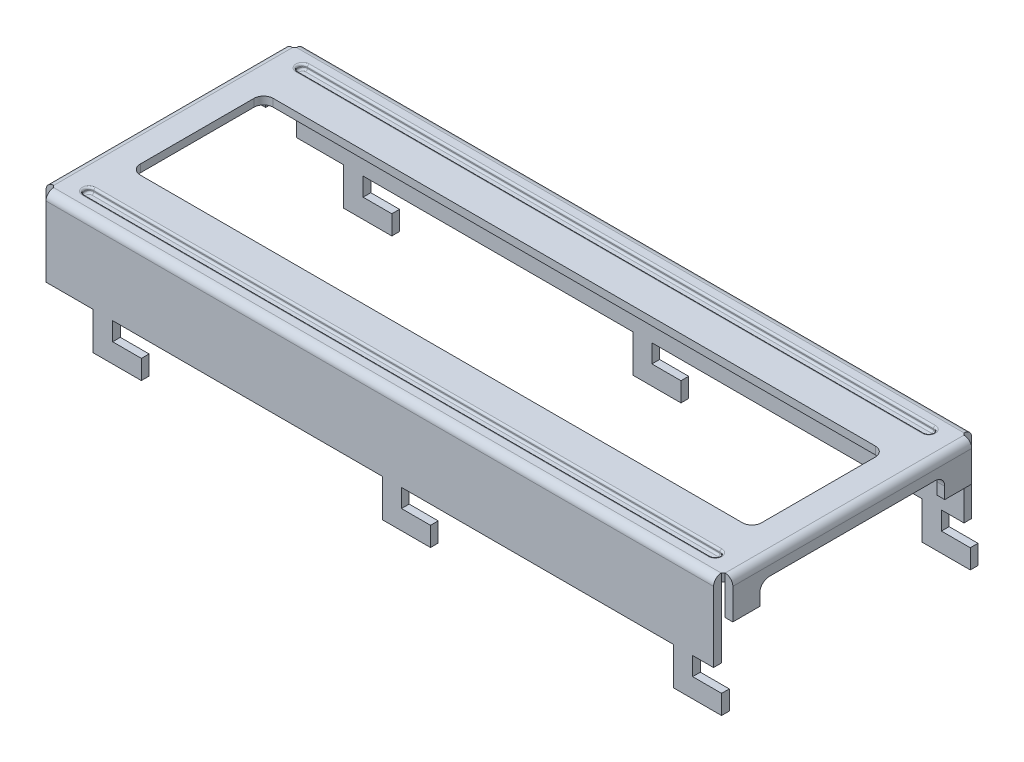
SolidWorks part; units mm, degrees
ref_plane "Front Plane" through (0, 0, 0) normal (0, 0, 1) x (1, 0, 0)
ref_plane "Top Plane" through (0, 0, 0) normal (0, 1, 0) x (1, 0, 0)
ref_plane "Right Plane" through (0, 0, 0) normal (1, 0, 0) x (0, 0, -1)
sketch "Sketch1" plane through (0, 0, 0) normal (0, 1, 0) x (1, 0, 0)
  line L1 (-35.65, 13.4) -> (35.65, 13.4)
  line L2 (-35.65, 13.4) -> (-35.65, -13.4)
  line L3 (-35.65, -13.4) -> (35.65, -13.4)
  line L4 (35.65, 13.4) -> (35.65, -13.4)
extrude "Boss-Extrude1" add sketch "Sketch1" along normal blind 0.8
sketch "Sketch2" plane through (0, 0, 0) normal (0, -1, 0) x (1, 0, 0)
  line L8 (34.85, -12.6) -> (34.85, 12.6)
  line L9 (34.85, 12.6) -> (-34.85, 12.6)
  line L10 (-34.85, 12.6) -> (-34.85, -12.6)
  line L11 (-34.85, -12.6) -> (34.85, -12.6)
  line L12 (34.85, -12.6) -> (34.85, 12.6)
  line L13 (34.85, 12.6) -> (-34.85, 12.6)
  line L14 (-34.85, 12.6) -> (-34.85, -12.6)
  line L15 (-34.85, -12.6) -> (34.85, -12.6)
  line L16 (35.65, -13.4) -> (35.65, 13.4)
  line L17 (35.65, 13.4) -> (-35.65, 13.4)
  line L18 (-35.65, 13.4) -> (-35.65, -13.4)
  line L19 (-35.65, -13.4) -> (35.65, -13.4)
  line L20 (35.65, -13.4) -> (35.65, 13.4)
  line L21 (35.65, 13.4) -> (-35.65, 13.4)
  line L22 (-35.65, 13.4) -> (-35.65, -13.4)
  line L23 (-35.65, -13.4) -> (35.65, -13.4)
  dimension "D1" = 0.8
  dimension "D2" = 0
extrude "Boss-Extrude2" add sketch "Sketch2" along normal blind 7.3
sketch "Sketch5" plane through (-35.65, 0, 0) normal (-1, 0, 0) x (0, 0, 1)
  line L11 (-12.4, 0) -> (-12.6, 0)
  line L12 (-12.6, -7.3) -> (-12.6, 0)
  line L13 (-12.4, 0) -> (-12.4, -3.2)
  line L14 (-12.4, -3.2) -> (-9.6, -3.2)
  line L15 (-9.6, -3.2) -> (-9.6, -2)
  line L16 (12.6, 0) -> (12.6, -7.3)
  line L17 (12.6, 0) -> (12.4, 0)
  line L18 (12.4, -3.2) -> (12.4, 0)
  line L19 (9.6, -3.2) -> (12.4, -3.2)
  line L20 (9.6, -2) -> (9.6, -3.2)
  line L21 (-8.6, -1) -> (8.6, -1)
  line L22 (-12.6, -7.3) -> (12.6, -7.3)
  line L25 (13.4, 0.8) -> (13.4, 0)
  line L26 (12.6, 0.8) -> (13.4, 0.8)
  line L29 (-12.6, 0.8) -> (-13.4, 0.8)
  line L30 (-13.4, 0.8) -> (-13.4, 0)
  arc A2 (-8.6, -1) -> (-9.6, -2) centre (-8.6, -2) ccw
  arc A3 (9.6, -2) -> (8.6, -1) centre (8.6, -2) ccw
  arc A5 (13.4, 0) -> (12.6, 0.8) centre (12.6, 0) ccw
  arc A7 (-12.6, 0.8) -> (-13.4, 0) centre (-12.6, 0) ccw
extrude "Cut-Extrude1" cut sketch "Sketch5" against normal through all
sketch "Sketch9" plane through (0, 0, 13.4) normal (0, 0, 1) x (1, 0, 0)
  line L0 (-35.65, 0.8) -> (-34.85, 0.8)
  line L1 (34.65, -7.3) -> (34.65, 0)
  line L2 (-34.65, 0) -> (-34.65, -7.3)
  line L3 (-34.65, 0) -> (-34.85, 0)
  line L4 (35.65, 0.8) -> (35.65, 0)
  line L5 (-35.65, 0.8) -> (-35.65, 0)
  line L6 (34.65, -7.3) -> (35.65, -7.3)
  line L7 (35.65, -3.2) -> (35.65, -7.3)
  line L8 (-34.65, -7.3) -> (-35.65, -7.3)
  line L9 (-35.65, -3.2) -> (-35.65, -7.3)
  line L10 (-35.65, -3.2) -> (-34.85, -3.2)
  line L11 (-34.85, -3.2) -> (-34.85, 0)
  line L12 (34.85, 0) -> (34.65, 0)
  line L13 (34.85, 0) -> (34.85, -3.2)
  line L14 (34.85, -3.2) -> (35.65, -3.2)
  line L15 (34.65, 0) -> (34.85, 0)
  line L16 (35.65, -7.3) -> (35.65, -3.2)
  line L17 (-35.65, -7.3) -> (-34.65, -7.3)
  line L18 (34.85, 0.8) -> (35.65, 0.8)
  line L19 (-35.65, -3.2) -> (-35.65, -7.3)
  arc A0 (-34.85, 0.8) -> (-35.65, 0) centre (-34.85, 0) ccw
  arc A1 (35.65, 0) -> (34.85, 0.8) centre (34.85, 0) ccw
  line M2 (35.65, 0) -> (-35.65, 0)
  line M3 (-35.65, 0) -> (-35.65, -7.3)
  line M4 (-35.65, -7.3) -> (35.65, -7.3)
  line M5 (35.65, -7.3) -> (35.65, 0)
extrude "Cut-Extrude4" cut sketch "Sketch9" against normal through all contours A0 L0 L5 | L11 L10 L2 M3 M4 M2 | L14 L13 L1 M2 M4 M5 | L4 A1 L18
sketch "Sketch10" plane through (0, 0.8, 0) normal (0, 1, 0) x (1, 0, 0)
  line L0 (-34.65, -12.6) -> (-34.65, -13.4) construction
  line L1 (-34.65, -12.6) -> (-34.65, -13.4)
  line L2 (-34.85, -12.4) -> (-35.65, -12.4) construction
  line L3 (-34.85, -12.4) -> (-35.65, -12.4)
  line L4 (-34.65, -12.6) -> (-34.85, -12.4)
  line L7 (-35.65, -12.4) -> (-35.65, -13.4)
  line L8 (-35.65, -12.6) -> (-35.65, -13.4) construction
  line L9 (-35.65, -13.4) -> (-34.65, -13.4)
  line L10 (35.65, -13.4) -> (34.65, -13.4)
  line L11 (35.65, -12.4) -> (35.65, -13.4)
  line L12 (34.65, -12.6) -> (34.85, -12.4)
  line L13 (34.85, -12.4) -> (35.65, -12.4)
  line L14 (34.65, -12.6) -> (34.65, -13.4)
  line L15 (34.65, 12.6) -> (34.65, 13.4)
  line L16 (34.85, 12.4) -> (35.65, 12.4)
  line L17 (34.65, 12.6) -> (34.85, 12.4)
  line L18 (35.65, 12.4) -> (35.65, 13.4)
  line L19 (35.65, 13.4) -> (34.65, 13.4)
  line L20 (-35.65, 13.4) -> (-34.65, 13.4)
  line L21 (-35.65, 12.4) -> (-35.65, 13.4)
  line L22 (-34.65, 12.6) -> (-34.85, 12.4)
  line L23 (-34.85, 12.4) -> (-35.65, 12.4)
  line L24 (-34.65, 12.6) -> (-34.65, 13.4)
  point P10 (0, 0)
extrude "Cut-Extrude5" cut sketch "Sketch10" against normal through all
sketch "Sketch13" plane through (0, -7.3, 0) normal (0, -1, 0) x (1, 0, 0)
  line L0 (32.4798, 12.6) -> (32.4798, 13.4)
  line L1 (30.4798, 12.6) -> (32.4798, 12.6)
  line L2 (30.4798, 13.4) -> (30.4798, 12.6)
  line L3 (32.4798, 13.4) -> (30.4798, 13.4)
  line L4 (32.302, -12.6) -> (32.302, -13.4)
  line L5 (32.4798, 13.4) -> (32.4798, 12.6)
  line L6 (2.25, -12.6) -> (0.2673, -12.6)
  line L7 (0.2673, -13.4) -> (2.25, -13.4)
  line L8 (-27.7327, -12.6) -> (-29.75, -12.6)
  line L9 (2.25, 13.4) -> (2.25, 12.6)
  line L10 (-29.75, -13.4) -> (-27.7327, -13.4)
  line L11 (30.4798, 12.6) -> (30.4798, 13.4)
  line L13 (0.2673, 12.6) -> (0.2673, 13.4)
  line L15 (-27.7327, 13.4) -> (-27.7327, 12.6)
  line L17 (-29.75, 12.6) -> (-29.75, 13.4)
  line L20 (-34.65, -12.6) -> (34.65, -12.6) construction
  line L21 (-34.65, -13.4) -> (34.65, -13.4) construction
  line L22 (34.65, 12.6) -> (-34.65, 12.6) construction
  line L23 (34.65, 13.4) -> (-34.65, 13.4) construction
  line L24 (-29.75, 13.4) -> (-27.7327, 13.4)
  line L25 (-27.7327, 12.6) -> (-29.75, 12.6)
  line L26 (0.2673, 13.4) -> (2.25, 13.4)
  line L27 (2.25, 12.6) -> (0.2673, 12.6)
  line L28 (32.4798, 12.6) -> (32.4798, 13.4)
  line L29 (-29.75, -12.6) -> (-29.75, -13.4)
  line L30 (-27.7327, -13.4) -> (-27.7327, -12.6)
  line L31 (0.2673, -12.6) -> (0.2673, -13.4)
  line L32 (30.302, -12.6) -> (30.302, -13.4)
  line L33 (2.25, -13.4) -> (2.25, -12.6)
  line L34 (32.302, -13.4) -> (32.302, -12.6)
  line L35 (32.302, -13.4) -> (30.302, -13.4)
  line L36 (30.302, -13.4) -> (30.302, -12.6)
  line L37 (30.302, -12.6) -> (32.302, -12.6)
  line L38 (32.302, -12.6) -> (32.302, -13.4)
  point P17 (0, 0)
  point P19 (0, 0)
  point P33 (0, 0)
  point P34 (0, 0)
  point P37 (0, 0)
  point P38 (0, 0)
  point P39 (0, 0)
  line M3 (34.65, 13.4) -> (-34.65, 13.4)
  line M5 (-34.65, 12.6) -> (34.65, 12.6)
  dimension "D1" = 2
  dimension "D2" = 2
extrude "Bitis" add sketch "Sketch13" along normal blind 1.9 contours L2 L0 M3 M5 | L37 L32 L35 L4 | L7 L33 L6 L31 | L24 L15 L25 L17 | L27 L13 L26 L9 | L8 L29 L10 L30
sketch "Sketch14" plane through (0, -9.2, 0) normal (0, -1, 0) x (1, 0, 0)
  line L0 (30.302, -12.6) -> (30.302, -13.4) construction
  line L8 (-29.75, 13.4) -> (-29.75, 12.6)
  line L9 (-29.75, 12.6) -> (-24.75, 12.6)
  line L10 (-24.75, 12.6) -> (-24.75, 13.4)
  line L11 (-24.75, 13.4) -> (-29.75, 13.4)
  line L12 (0.2673, -13.4) -> (5.2673, -13.4)
  line L13 (-24.75, -13.4) -> (-24.75, -12.6)
  line L14 (5.2673, 12.6) -> (5.2673, 13.4)
  line L15 (5.2673, 13.4) -> (0.2673, 13.4)
  line L16 (0.2673, 13.4) -> (0.2673, 12.6)
  line L17 (0.2673, 12.6) -> (5.2673, 12.6)
  line L18 (35.4798, 13.4) -> (30.4798, 13.4)
  line L19 (30.4798, 13.4) -> (30.4798, 12.6)
  line L20 (30.4798, 12.6) -> (35.4798, 12.6)
  line L21 (35.4798, 12.6) -> (35.4798, 13.4)
  line L22 (-24.75, -12.6) -> (-29.75, -12.6)
  line L23 (-29.75, -12.6) -> (-29.75, -13.4)
  line L24 (-29.75, -13.4) -> (-24.75, -13.4)
  line L25 (5.2673, -13.4) -> (5.2673, -12.6)
  line L26 (5.2673, -12.6) -> (0.2673, -12.6)
  line L27 (0.2673, -12.6) -> (0.2673, -13.4)
  line L28 (35.302, -12.6) -> (30.302, -12.6)
  line L29 (30.302, -12.6) -> (30.302, -13.4)
  line L30 (30.302, -13.4) -> (35.302, -13.4)
  line L31 (35.302, -13.4) -> (35.302, -12.6)
  point P2 (0, 0)
  point P26 (0, 0)
  point P28 (0, 0)
  point P30 (0, 0)
  point P31 (0, 0)
  point P34 (0, 0)
  dimension "D1" = 5
  dimension "D2" = 5
extrude "Cokor" add sketch "Sketch14" along normal blind 2
sketch "Sketch15" plane through (0, 0.8, 0) normal (0, 1, 0) x (1, 0, 0)
  line L0 (-32.5, -11.0881) -> (32.5, -11.0881) construction
  line L1 (-32.5, -10.5881) -> (32.5, -10.5881)
  line L2 (-32.5, -11.5881) -> (32.5, -11.5881)
  arc A0 (-32.5, -10.5881) -> (-32.5, -11.5881) centre (-32.5, -11.0881) ccw
  arc A1 (32.5, -11.5881) -> (32.5, -10.5881) centre (32.5, -11.0881) ccw
  point P0 (0, -11.0881)
extrude "Cut-Extrude6" cut sketch "Sketch15" against normal blind 0.5
fillet "Fillet1" radius 0.2 8 edges at (-33, 0.8, 11.0881) (0, 0.8, 10.5881) (33, 0.8, 11.0881) (0, 0.8, 11.5881) (-33, 0.3, 11.0881) (33, 0.3, 11.0881) (0, 0.3, 10.5881) (0, 0.3, 11.5881)
sketch "Sketch16" plane through (0, 0.8, 0) normal (0, 1, 0) x (1, 0, 0)
  line L0 (-42.574, 0) -> (42.574, 0) construction
  point P4 (0, 0)
ref_plane "Plane1" through (0, 0, 0) normal (0, 0, 1) x (1, 0, 0)
mirror "Mirror1" about plane through (0, 0, 0) normal (0, 0, 1) of "Cut-Extrude6", "Fillet1"
sketch "Sketch19" plane through (0, 0.8, 0) normal (0, 1, 0) x (1, 0, 0)
  line L0 (-31.2804, -6.9799) -> (31.2196, -6.9799)
  line L1 (-32.2804, 5.8201) -> (-32.2804, -5.9799)
  line L2 (31.2196, 6.8201) -> (-31.2804, 6.8201)
  line L3 (32.2196, -5.9799) -> (32.2196, 5.8201)
  arc A0 (-32.2804, -5.9799) -> (-31.2804, -6.9799) centre (-31.2804, -5.9799) ccw
  arc A1 (-31.2804, 6.8201) -> (-32.2804, 5.8201) centre (-31.2804, 5.8201) ccw
  arc A2 (32.2196, 5.8201) -> (31.2196, 6.8201) centre (31.2196, 5.8201) ccw
  arc A3 (31.2196, -6.9799) -> (32.2196, -5.9799) centre (31.2196, -5.9799) ccw
extrude "Cut-Extrude7" cut sketch "Sketch19" against normal up to next
